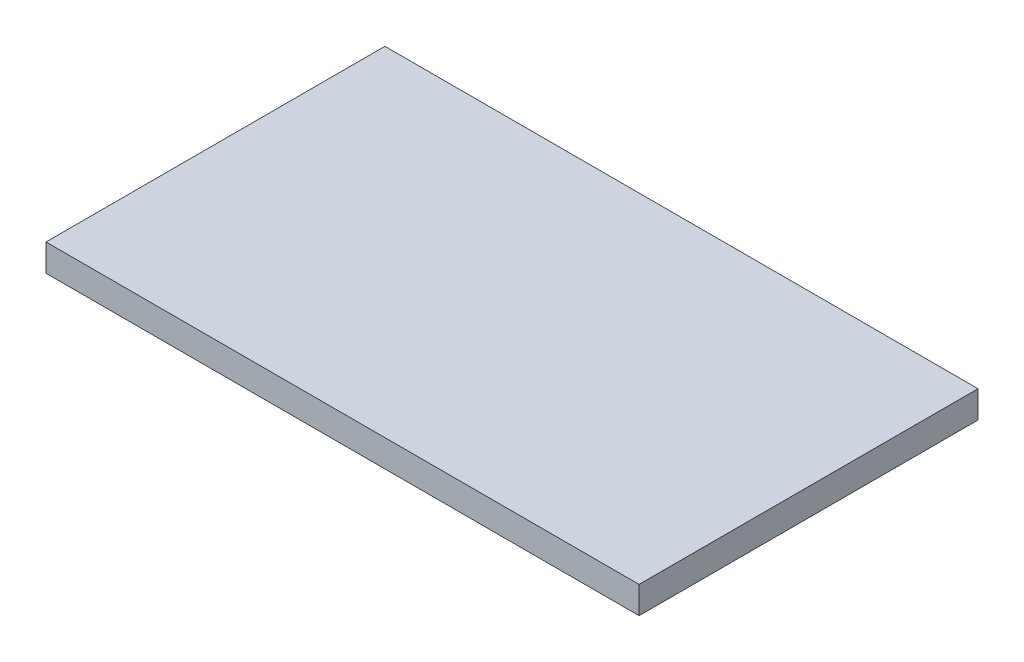
SolidWorks part; units mm, degrees
ref_plane "Front" through (0, 0, 0) normal (0, 0, 1) x (1, 0, 0)
ref_plane "Top" through (0, 0, 0) normal (0, 1, 0) x (1, 0, 0)
ref_plane "Right" through (0, 0, 0) normal (1, 0, 0) x (0, 0, -1)
sketch "Sketch1" plane through (0, 0, 0) normal (0, 1, 0) x (1, 0, 0)
  line L1 (0, 0) -> (35, 0)
  line L2 (0, 0) -> (0, 20)
  line L3 (0, 20) -> (35, 20)
  line L4 (35, 0) -> (35, 20)
  dimension "D1" = 35
  dimension "D2" = 20
extrude "Boss-Extrude1" add sketch "Sketch1" along normal blind 1.6
